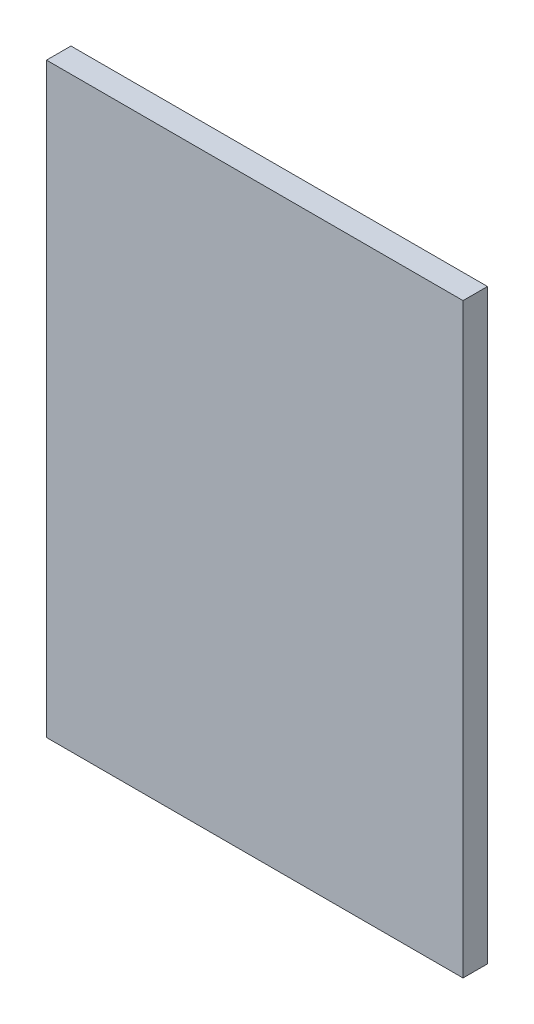
SolidWorks part; units mm, degrees
material "6061 Alloy"
ref_plane "Front Plane" through (0, 0, 0) normal (0, 0, 1) x (1, 0, 0)
ref_plane "Top Plane" through (0, 0, 0) normal (0, 1, 0) x (1, 0, 0)
ref_plane "Right Plane" through (0, 0, 0) normal (1, 0, 0) x (0, 0, -1)
sketch "Sketch1" plane through (0, 0, 0) normal (0, 0, 1) x (1, 0, 0)
  line L1 (-54.102, 6.2266) -> (0, 6.2266)
  line L2 (-54.102, 6.2266) -> (-54.102, 82.4266)
  line L3 (-54.102, 82.4266) -> (0, 82.4266)
  line L4 (0, 6.2266) -> (0, 82.4266)
  dimension "D1" = 54.102
  dimension "D2" = 76.2
extrude "Boss-Extrude2" add sketch "Sketch1" along normal blind 3.175
